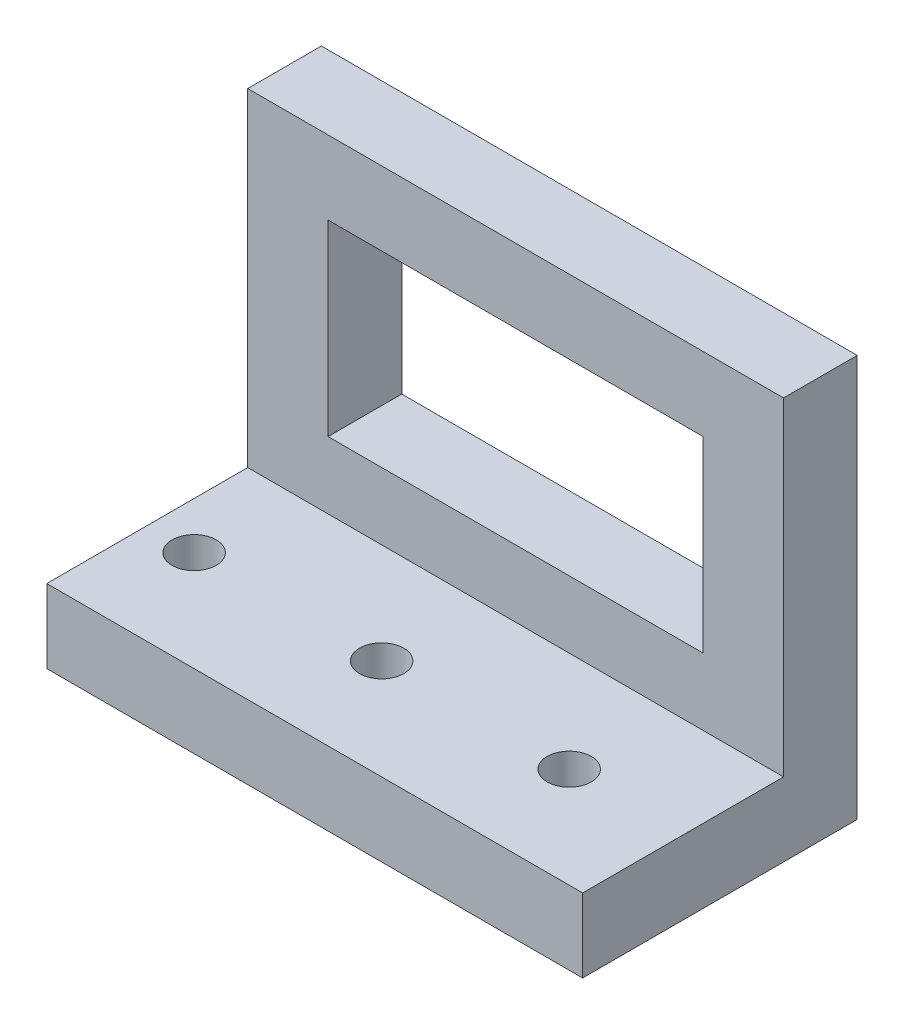
SolidWorks part; units mm, degrees
ref_plane "Front" through (0, 0, 0) normal (0, 0, 1) x (1, 0, 0)
ref_plane "Top" through (0, 0, 0) normal (0, 1, 0) x (1, 0, 0)
ref_plane "Right" through (0, 0, 0) normal (1, 0, 0) x (0, 0, -1)
sketch "Sketch1" plane through (0, 0, 0) normal (0, 0, 1) x (1, 0, 0)
  line L1 (-20.2222, 10.7222) -> (19.7778, 10.7222)
  line L2 (-20.2222, 10.7222) -> (-20.2222, -19.2778)
  line L3 (-20.2222, -19.2778) -> (19.7778, -19.2778)
  line L4 (19.7778, 10.7222) -> (19.7778, -19.2778)
  dimension "D1" = 40
  dimension "D2" = 30
extrude "Boss-Extrude1" add sketch "Sketch1" along normal blind 5.5
sketch "Sketch4" plane through (0, 0, 5.5) normal (0, 0, 1) x (1, 0, 0)
  line L0 (-20.2222, 10.7222) -> (-20.2222, -19.2778) construction
  line L2 (-14.2222, -8.7778) -> (-14.2222, 5.2222)
  line L3 (-14.2222, 5.2222) -> (13.7778, 5.2222)
  line L4 (13.7778, -8.7778) -> (13.7778, 5.2222)
  line L7 (-14.2222, -8.7778) -> (13.7778, -8.7778)
  line L9 (19.7778, 10.7222) -> (-20.2222, 10.7222) construction
  dimension "D1" = 28
  dimension "D2" = 14
  dimension "D3" = 6
  dimension "D4" = 5.5
extrude "Cut-Extrude1" cut sketch "Sketch4" against normal blind 5.5
sketch "Sketch5" plane through (0, 0, 5.5) normal (0, 0, 1) x (1, 0, 0)
  line L0 (19.7778, -19.2778) -> (19.7778, 10.7222) construction
  line L1 (-20.2222, -19.2778) -> (19.7778, -19.2778)
  line L2 (-20.2222, -19.2778) -> (-20.2222, -13.7778)
  line L3 (-20.2222, -13.7778) -> (19.7778, -13.7778)
  line L4 (19.7778, -19.2778) -> (19.7778, -13.7778)
  dimension "D1" = 5.5
extrude "Boss-Extrude2" add sketch "Sketch5" along normal blind 15
sketch "Sketch6" plane through (0, -19.2778, 0) normal (0, -1, 0) x (1, 0, 0)
  line L1 (-20.2222, 20.5) -> (-20.2222, 0) construction
  circle A0 centre (-16.7222, 13) radius 1.65
  circle A1 centre (-2.7222, 13) radius 1.65
  circle A2 centre (11.2778, 13) radius 1.65
  dimension "D1" = 3.3
  dimension "D2" = 3.5
  dimension "D3" = 3
extrude "Cut-Extrude3" cut sketch "Sketch6" against normal blind 15
